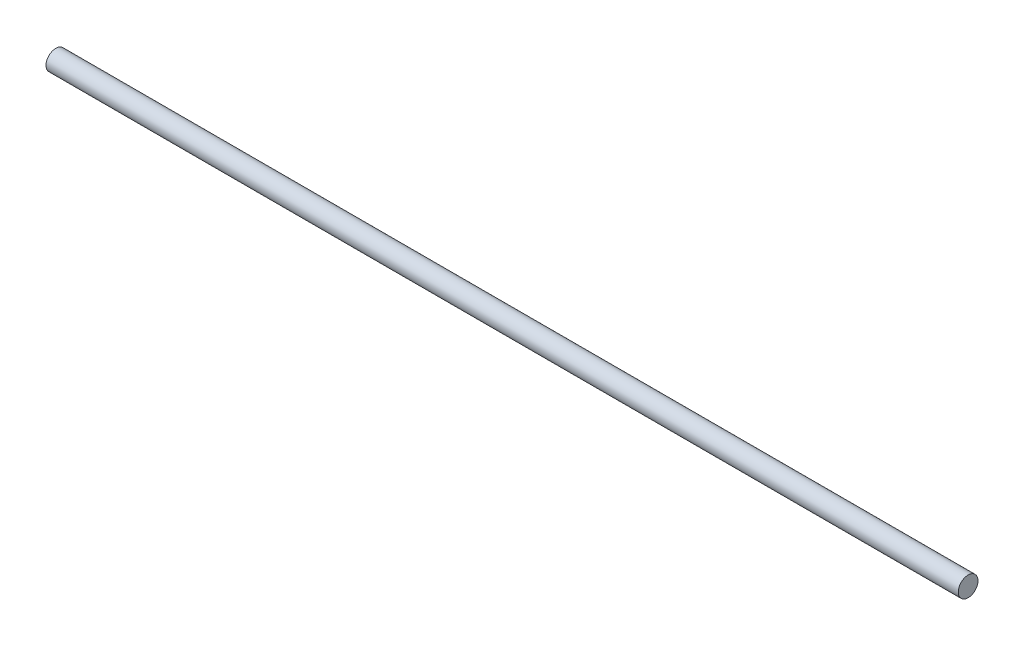
SolidWorks part; units mm, degrees
material "1060 合金"
ref_plane "前视基准面" through (0, 0, 0) normal (0, 0, 1) x (1, 0, 0)
ref_plane "上视基准面" through (0, 0, 0) normal (0, 1, 0) x (1, 0, 0)
ref_plane "右视基准面" through (0, 0, 0) normal (1, 0, 0) x (0, 0, -1)
other "Configuration Table"
sketch "草图1" plane through (0, 0, 0) normal (1, 0, 0) x (0, 0, -1)
  circle A0 centre (0, 0) radius 4
  dimension "D1" = 8
extrude "凸台-拉伸1" add sketch "草图1" along normal blind 370
